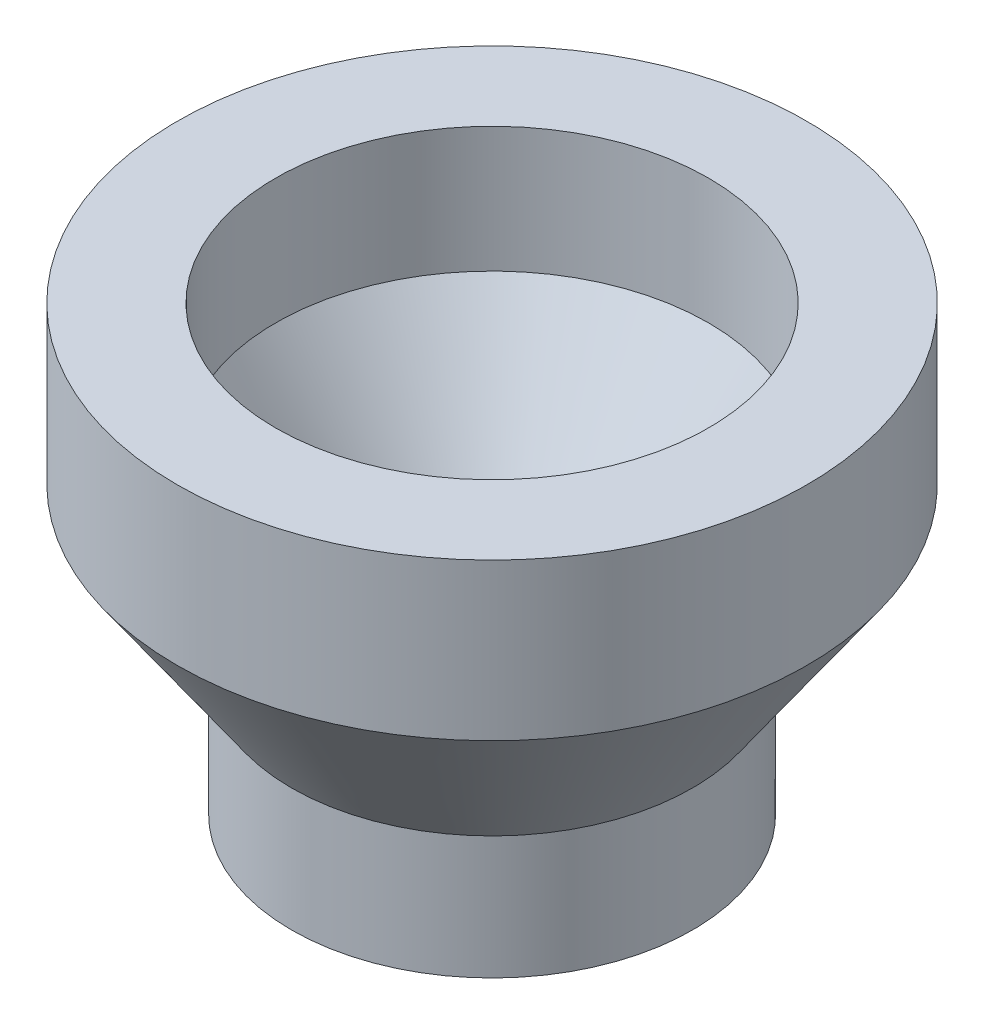
SolidWorks part; units mm, degrees
ref_plane "前视基准面" through (0, 0, 0) normal (0, 0, 1) x (1, 0, 0)
ref_plane "上视基准面" through (0, 0, 0) normal (0, 1, 0) x (1, 0, 0)
ref_plane "右视基准面" through (0, 0, 0) normal (1, 0, 0) x (0, 0, -1)
other "Configuration Table"
sketch "草图1" plane through (0, 0, 0) normal (0, 0, 1) x (1, 0, 0)
  line L0 (0, 71.4915) -> (0, -8.0002) construction
  line L1 (-2.575, 25.4373) -> (-2.575, 29.282)
  line L2 (-2.575, 29.282) -> (-4.4, 31.8883)
  line L3 (-4.4, 31.8883) -> (-4.4, 34.4373)
  line L4 (10, 34.4373) -> (-10, 34.4373) construction
  line L5 (-4.4, 34.4373) -> (-6.4, 34.4373)
  line L6 (-6.4, 34.4373) -> (-6.4, 31.2577)
  line L7 (-6.4, 31.2577) -> (-4.075, 27.9373)
  line L8 (-4.075, 27.9373) -> (-4.075, 25.4373)
  line L9 (-4.075, 25.4373) -> (-2.575, 25.4373)
  line L11 (-6.5, 25.4373) -> (6.5, 25.4373) construction
  dimension "D1" = 5.15
  dimension "D2" = 1.5
  dimension "D3" = 2
  dimension "D4" = 12.8
  dimension "D5" = 2
  dimension "D6" = 2.5
  dimension "D7" = 35
revolve "旋转1" add sketch "草图1" angle 360 about L0
